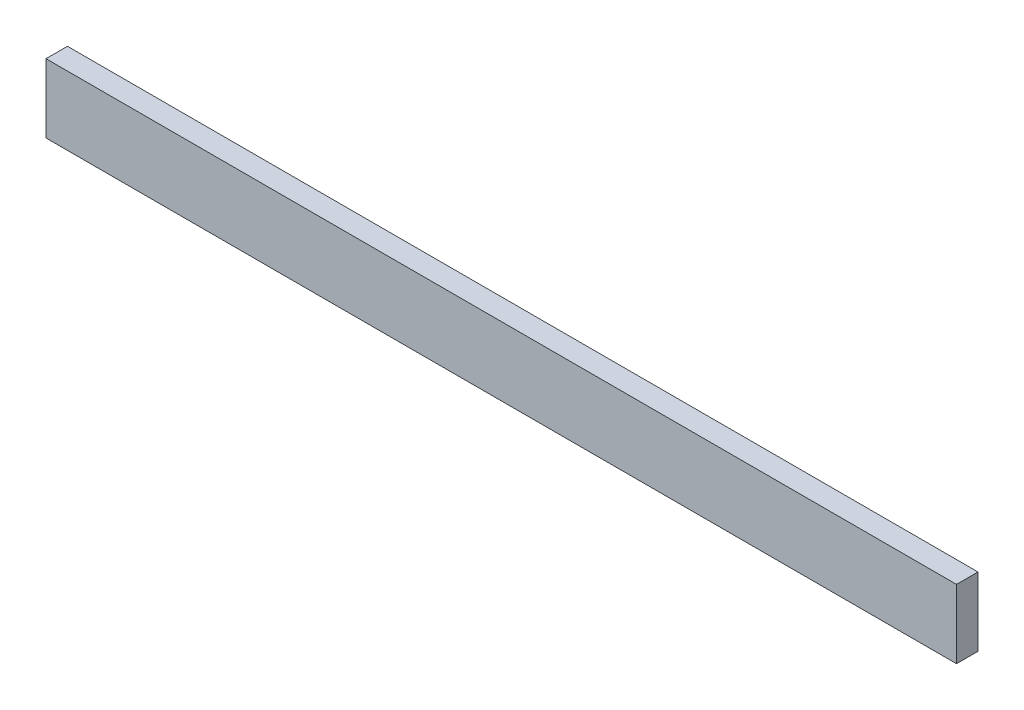
SolidWorks part; units mm, degrees
ref_plane "Alzado" through (0, 0, 0) normal (0, 0, 1) x (1, 0, 0)
ref_plane "Planta" through (0, 0, 0) normal (0, 1, 0) x (1, 0, 0)
ref_plane "Vista lateral" through (0, 0, 0) normal (1, 0, 0) x (0, 0, -1)
sketch "Croquis_faldon" plane through (0, 0, 0) normal (0, 1, 0) x (1, 0, 0)
  line L1 (-530, -12.5) -> (530, -12.5)
  line L2 (-530, -12.5) -> (-530, 12.5)
  line L3 (-530, 12.5) -> (530, 12.5)
  line L4 (530, -12.5) -> (530, 12.5)
  line L5 (-530, -12.5) -> (530, 12.5) construction
  line L6 (-530, 12.5) -> (530, -12.5) construction
  point P0 (0, 0)
  dimension "D1" = 530
  dimension "D2" = 12.5
extrude "Faldon_largo" add sketch "Croquis_faldon" along normal blind 80
